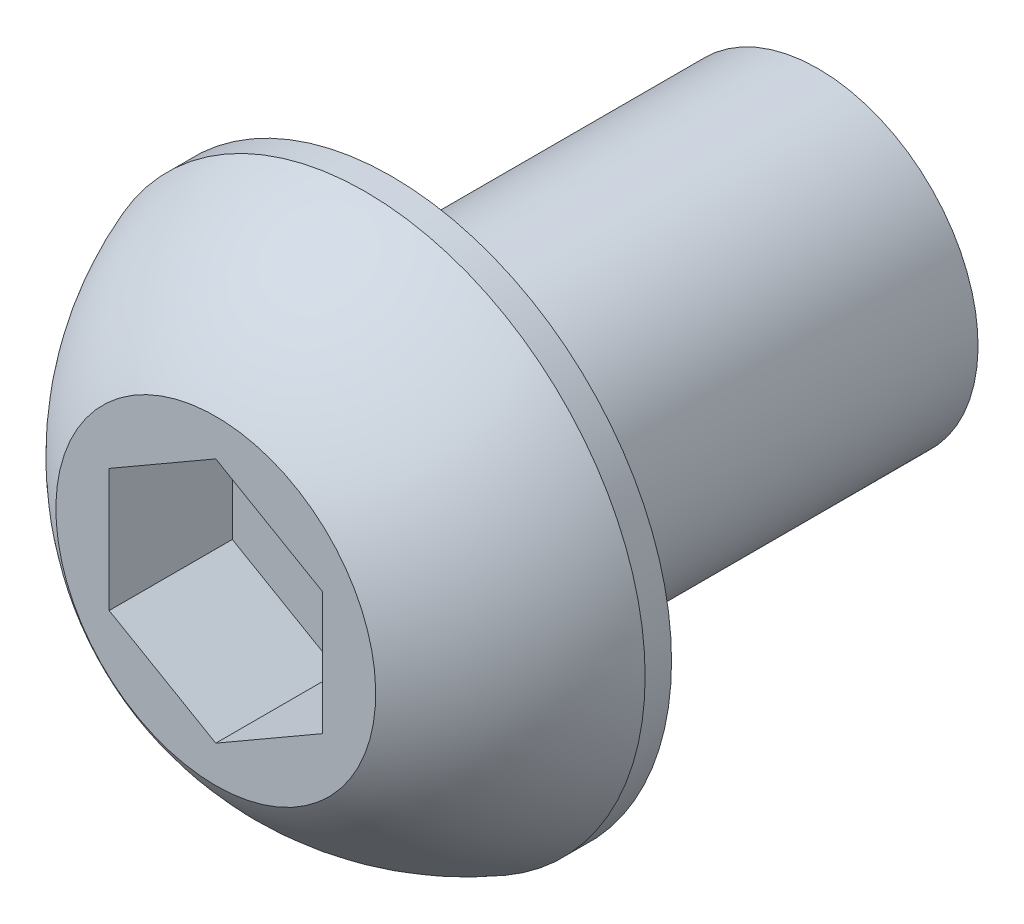
SolidWorks part; units mm, degrees
material "Chrome Stainless Steel"
ref_plane "Front" through (0, 0, 0) normal (0, 0, 1) x (1, 0, 0)
ref_plane "Top" through (0, 0, 0) normal (0, 1, 0) x (1, 0, 0)
ref_plane "Right" through (0, 0, 0) normal (1, 0, 0) x (0, 0, -1)
sketch "Sketch1" plane through (0, 0, 0) normal (1, 0, 0) x (0, 0, -1)
  line L2 (3.3, 3) -> (11.3, 3)
  line L3 (11.3, 3) -> (11.3, 0)
  line L4 (11.3, 0) -> (3.3, 0)
  line L6 (2.805, 5.25) -> (3.3, 5.25) construction
  line L7 (11.3, 3) -> (11.3, -3) construction
  line L8 (0, 0) -> (3.3, 0) construction
  line L9 (3.3, 5.25) -> (3.3, -5.25) construction
  line L11 (3.3, 3) -> (3.3, 0)
  line L13 (0, 2) -> (0, -2) construction
  line L14 (0, 2) -> (0, 3) construction
  arc A3 (0, 3) -> (2.805, 5.25) centre (4.7113, 0) cw construction
  dimension "D1" = 0.495
revolve "Revolve1" add sketch "Sketch1" angle 360 mid plane about L4
sketch "Sketch7" plane through (0, 0, 0) normal (1, 0, 0) x (0, 0, -1)
  line L6 (2.805, 5.25) -> (3.3, 5.25) construction
  line L8 (0, 0) -> (3.3, 0) construction
  line L11 (3.3, 5.25) -> (3.3, -5.25) construction
  line L12 (2.805, 5.25) -> (3.3, 5.25)
  line L13 (0, 0) -> (3.3, 0)
  line L14 (0, 2) -> (0, -2) construction
  line L15 (3.3, 5.25) -> (3.3, 0)
  line L16 (0, 3) -> (0, 0)
  arc A2 (2.805, 5.25) -> (0, 3) centre (4.7113, 0) ccw construction
  arc A3 (2.805, 5.25) -> (0, 3) centre (4.7113, 0) ccw
revolve "Revolve2" add sketch "Sketch7" angle 360 mid plane about L13
sketch "Sketch5" plane through (0, 0, 0) normal (0, 0, 1) x (1, 0, 0)
  line L1 (2, -1.1547) -> (2, 1.1547)
  line L2 (2, 1.1547) -> (0, 2.3094)
  line L3 (0, 2.3094) -> (-2, 1.1547)
  line L4 (-2, 1.1547) -> (-2, -1.1547)
  line L5 (-2, -1.1547) -> (0, -2.3094)
  line L6 (0, -2.3094) -> (2, -1.1547)
  circle A0 centre (0, 0) radius 2 construction
extrude "Cut-Extrude2" cut sketch "Sketch5" against normal blind 2.31
equation "\"D1@Cut-Extrude2\" = \"Head Ht@Sketch1\" * .7"
equation "\"D1@Sketch1\" = \"Head Ht@Sketch1\" * .15"
